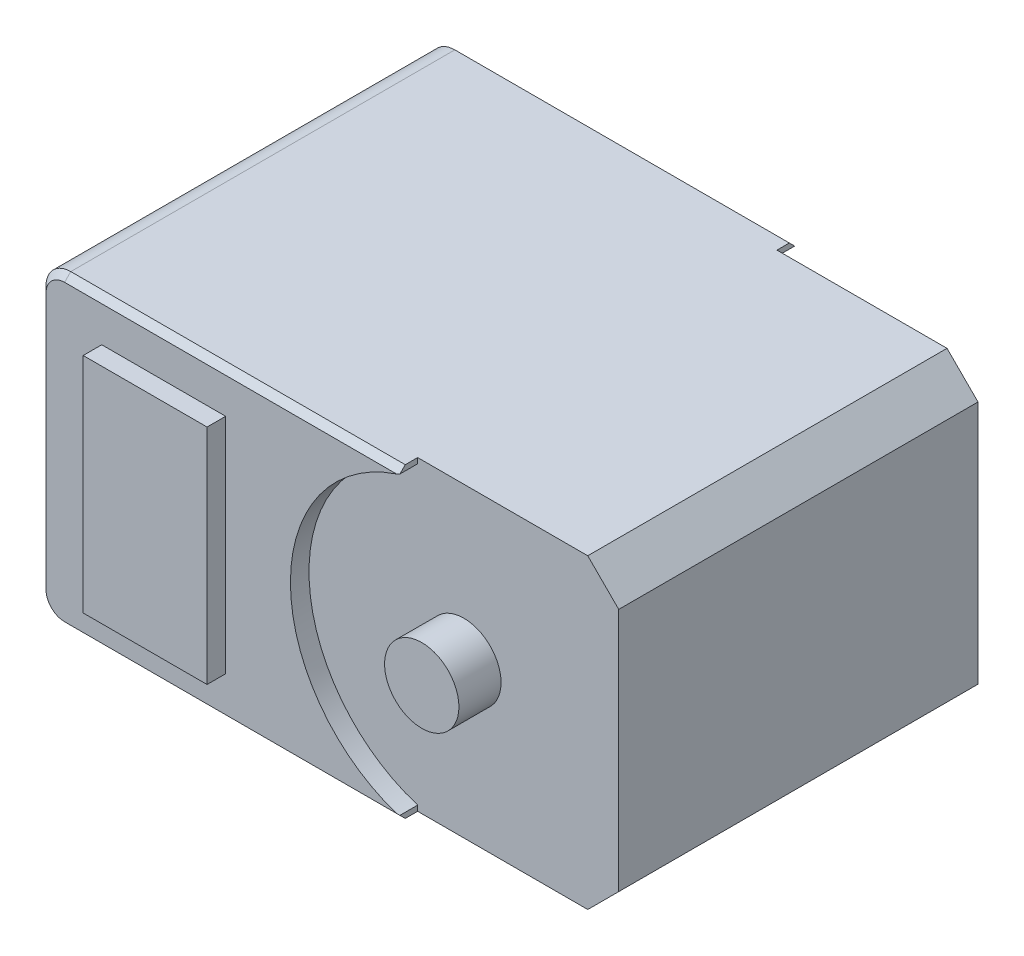
SolidWorks part; units mm, degrees
ref_plane "前视基准面" through (0, 0, 0) normal (0, 0, 1) x (1, 0, 0)
ref_plane "上视基准面" through (0, 0, 0) normal (0, 1, 0) x (1, 0, 0)
ref_plane "右视基准面" through (0, 0, 0) normal (1, 0, 0) x (0, 0, -1)
other "Configuration Table"
sketch "草图1" plane through (0, 0, 0) normal (0, 0, 1) x (1, 0, 0)
  line L1 (0, 0) -> (45.23, 0)
  line L2 (0, 0) -> (0, 24.73)
  line L3 (0, 24.73) -> (45.23, 24.73)
  line L4 (45.23, 0) -> (45.23, 24.73)
  dimension "D1" = 45.23
  dimension "D2" = 24.73
extrude "凸台-拉伸1" add sketch "草图1" along normal blind 35
sketch "草图2" plane through (0, 0, 0) normal (0, 0, 1) x (1, 0, 0)
  line L1 (45.23, 24.73) -> (30.8978, 24.73)
  line L2 (45.23, 24.73) -> (45.23, 0)
  line L3 (45.23, 0) -> (30.8978, 0)
  line L9 (0, 24.73) -> (0, 0)
  line L10 (0, 0) -> (45.23, 0)
  line L11 (45.23, 0) -> (45.23, 24.73)
  line L12 (45.23, 24.73) -> (0, 24.73)
  line L14 (30.8978, 0) -> (45.23, 0)
  line L15 (45.23, 0) -> (45.23, 24.73)
  line L16 (45.23, 24.73) -> (30.8978, 24.73)
  arc A0 (30.8978, 24.73) -> (30.8978, 0) centre (32.73, 12.365) ccw
  dimension "D2" = 0
extrude "切除-拉伸1" cut sketch "草图2" along normal blind 3 contours L1 A0 L3 L2
sketch "草图5" plane through (0, 0, 0) normal (0, 0, 1) x (1, 0, 0)
  line L0 (30.8978, 24.73) -> (0, 24.73) construction
  line L2 (0, 0) -> (0, 24.73)
  line L4 (29, 0) -> (29, 24.73)
  line L5 (30.8978, 0) -> (30.8978, 24.73)
  line L14 (30.8978, 24.73) -> (0, 24.73)
  line L15 (0, 0) -> (30.8978, 0)
  line L16 (0, 24.73) -> (0, 0)
  line L17 (30.8978, 24.73) -> (29, 24.73)
  line L18 (29, 0) -> (30.8978, 0)
  line L19 (0, 24.73) -> (0, 0)
  arc A4 (30.8978, 24.73) -> (30.8978, 0) centre (32.73, 12.365) ccw
  dimension "D1" = 29
  dimension "D3" = 0
extrude "切除-拉伸3" cut sketch "草图5" along normal up to surface (3 mm away) contours L4 L18 L5 L17 up to face at (35.397, 12.365, 3)
ref_plane "基准面1" through (0, 0, 17.5) normal (0, 0, 1) x (1, 0, 0)
mirror "镜向1" about plane through (0, 0, 17.5) normal (0, 0, 1) of "切除-拉伸3", "切除-拉伸1"
sketch "草图3" plane through (0, 0, 0) normal (0, 0, 1) x (1, 0, 0)
  arc A0 (29, 24.2955) -> (29, 0.4345) centre (32.73, 12.365) ccw construction
  arc A1 (29, 24.2955) -> (29, 0.4345) centre (32.73, 12.365) ccw
  circle A2 centre (32.73, 12.365) radius 3
  dimension "D1" = 6
extrude "凸台-拉伸2" add sketch "草图3" along normal blind 17.9 and the other way blind 18.6 from surface at 17.5 contours A2 starting at plane "基准面1"
sketch "草图4" plane through (0, 0, 0) normal (0, 0, 1) x (1, 0, 0)
  line L0 (0, 12.365) -> (51.1364, 12.365) construction
  line L1 (0, 24.73) -> (30.8978, 24.73)
  line L2 (0, 24.73) -> (0, 19.73)
  line L3 (0, 19.73) -> (30.8978, 19.73)
  line L4 (30.8978, 24.73) -> (30.8978, 19.73)
  line L5 (0, 24.73) -> (0, 0) construction
  line L6 (30.8978, 0) -> (30.8978, 5)
  line L7 (0, 0) -> (0, 5)
  line L8 (0, 0) -> (30.8978, 0)
  line L9 (0, 5) -> (30.8978, 5)
  dimension "D1" = 5
extrude "切除-拉伸2" cut sketch "草图4" along normal blind 1.5
chamfer "倒角1" distance 2.5 angle 45 2 edges at (45.23, 24.73, 17.5) (45.23, 0, 17.5)
fillet "圆角1" radius 2 2 edges at (0, 24.73, 18.25) (0, 0, 18.25)
sketch "草图6" plane through (0, 0, 35) normal (0, 0, 1) x (1, 0, 0)
  line L0 (-50.6859, 12.365) -> (-40.6859, 12.365) construction
  line L2 (0, 22.73) -> (0, 2) construction
  line L3 (5, 21.365) -> (15, 21.365)
  line L4 (5, 21.365) -> (5, 3.365)
  line L5 (5, 3.365) -> (15, 3.365)
  line L6 (15, 21.365) -> (15, 3.365)
  line L12 (29, 24.73) -> (2, 24.73)
  line L13 (0, 22.73) -> (0, 2)
  line L14 (2, 0) -> (29, 0)
  line L15 (29, 0) -> (29, 0.4345)
  line L16 (29, 24.2955) -> (29, 24.73)
  line L17 (29, 24.73) -> (2, 24.73)
  line L18 (0, 22.73) -> (0, 2)
  line L19 (2, 0) -> (29, 0)
  line L20 (29, 0) -> (29, 0.4345)
  line L21 (29, 24.2955) -> (29, 24.73)
  arc A3 (2, 24.73) -> (0, 22.73) centre (2, 22.73) ccw
  arc A5 (29, 24.2955) -> (29, 0.4345) centre (32.73, 12.365) ccw
  arc A8 (29, 24.2955) -> (29, 0.4345) centre (32.73, 12.365) ccw
  arc A9 (2, 24.73) -> (0, 22.73) centre (2, 22.73) ccw
  arc A10 (0, 2) -> (2, 0) centre (2, 2) ccw
  arc A11 (0, 2) -> (2, 0) centre (2, 2) ccw
  point P3 (-45.6859, 12.365)
  dimension "D1" = 9
  dimension "D2" = 0
  dimension "D3" = 5
  dimension "D4" = 10
extrude "切除-拉伸4" cut sketch "草图6" against normal blind 1.5
chamfer "倒角2" distance 0.5 angle 45 7 edges at (0, 21.23, 1.5) (15.5, 24.73, 1.5) (0, 12.365, 0) (0, 3.5, 1.5) (15.5, 0, 1.5) (15.5, 24.73, 33.5) (15.5, 0, 33.5)
